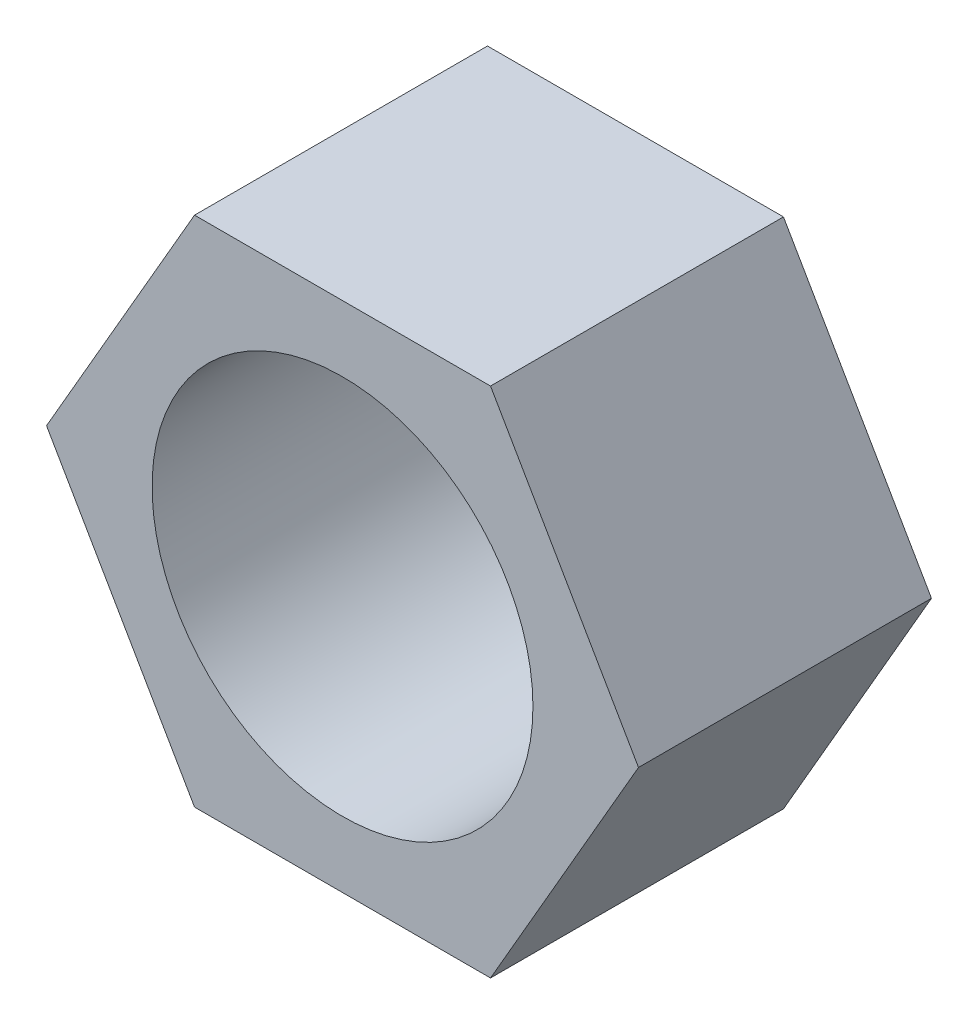
SolidWorks part; units mm, degrees
ref_plane "Front Plane" through (0, 0, 0) normal (0, 0, 1) x (1, 0, 0)
ref_plane "Top Plane" through (0, 0, 0) normal (0, 1, 0) x (1, 0, 0)
ref_plane "Right Plane" through (0, 0, 0) normal (1, 0, 0) x (0, 0, -1)
sketch "Sketch2" plane through (0, 0, 0) normal (0, 0, 1) x (1, 0, 0)
  line L1 (0.101, -0.175) -> (0.2021, 0)
  line L2 (0.2021, 0) -> (0.101, 0.175)
  line L3 (0.101, 0.175) -> (-0.101, 0.175)
  line L4 (-0.101, 0.175) -> (-0.2021, 0)
  line L5 (-0.2021, 0) -> (-0.101, -0.175)
  line L6 (-0.101, -0.175) -> (0.101, -0.175)
  circle A0 centre (0, 0) radius 0.175 construction
  circle A1 centre (0, 0) radius 0.13
  dimension "D1" = 0.26
  dimension "D2" = 0.35
extrude "Boss-Extrude1" add sketch "Sketch2" along normal blind 0.2
